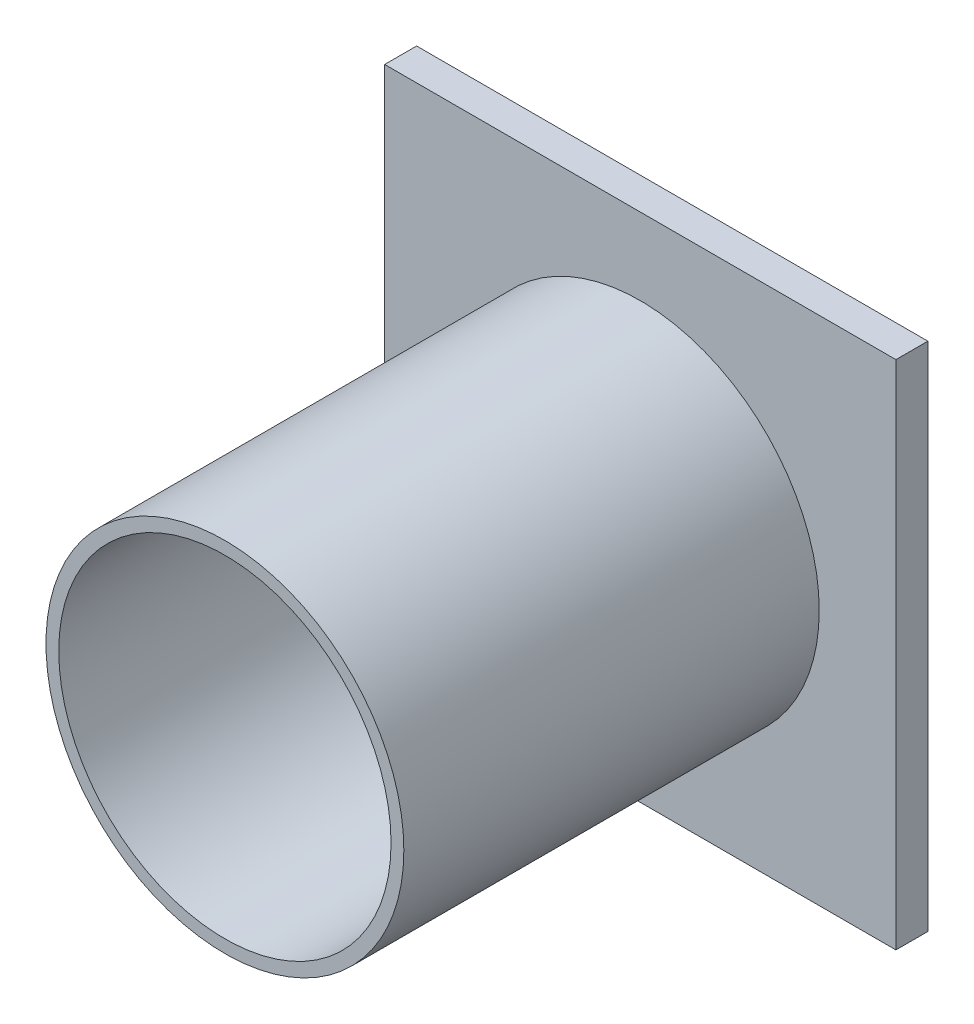
SolidWorks part; units mm, degrees
ref_plane "Front Plane" through (0, 0, 0) normal (0, 0, 1) x (1, 0, 0)
ref_plane "Top Plane" through (0, 0, 0) normal (0, 1, 0) x (1, 0, 0)
ref_plane "Right Plane" through (0, 0, 0) normal (1, 0, 0) x (0, 0, -1)
sketch "Sketch1" plane through (0, 0, 0) normal (0, 0, 1) x (1, 0, 0)
  line L1 (-29.9187, 28.9431) -> (50.0813, 28.9431)
  line L2 (-29.9187, 28.9431) -> (-29.9187, -51.0569)
  line L3 (-29.9187, -51.0569) -> (50.0813, -51.0569)
  line L4 (50.0813, 28.9431) -> (50.0813, -51.0569)
  dimension "D1" = 80
  dimension "D2" = 80
extrude "Boss-Extrude1" add sketch "Sketch1" along normal blind 5
sketch "Sketch2" plane through (0, 0, 5) normal (0, 0, 1) x (1, 0, 0)
  line L0 (50.0813, 28.9431) -> (-29.9187, 28.9431) construction
  line L1 (50.0813, -51.0569) -> (50.0813, 28.9431) construction
  circle A0 centre (10.0813, -11.0569) radius 26
  dimension "D3" = 52
  dimension "D1" = 40
  dimension "D2" = 40
extrude "Extrude-Thin1" add sketch "Sketch2" along normal blind 65 thin
